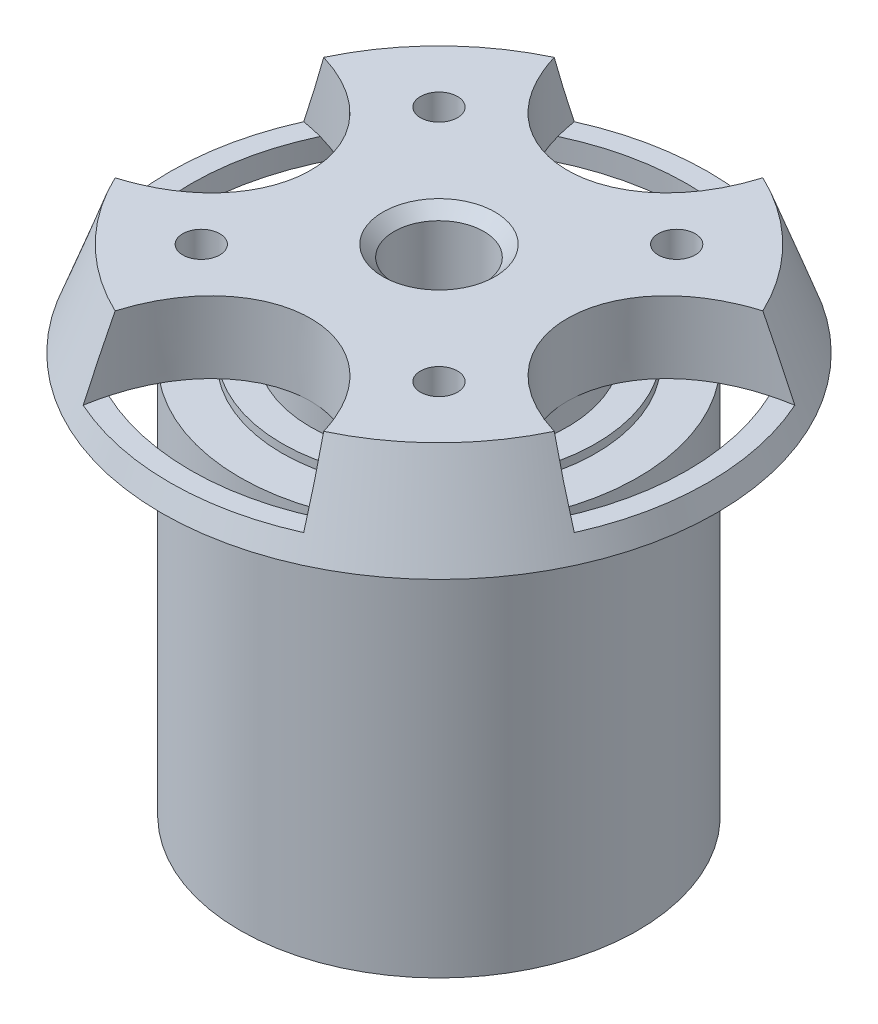
SolidWorks part; units mm, degrees
ref_plane "Front Plane" through (0, 0, 0) normal (0, 0, 1) x (1, 0, 0)
ref_plane "Top Plane" through (0, 0, 0) normal (0, 1, 0) x (1, 0, 0)
ref_plane "Right Plane" through (0, 0, 0) normal (1, 0, 0) x (0, 0, -1)
ref_axis "Axis1" through (0, 46.5537, 0) along (0, -1, 0)
sketch "Sketch2" plane through (0, 0, 0) normal (0, 0, 1) x (1, 0, 0)
  line L1 (0, 27.2574) -> (4, 27.2574)
  line L3 (4, 0) -> (21.6927, 0)
  line L4 (21.6927, 0) -> (24.75, -8.4)
  line L5 (24.75, -8.4) -> (14, -8.4)
  line L6 (14, -8.4) -> (14, -9.15)
  line L7 (14, -9.15) -> (17.75, -9.15)
  line L15 (17.75, -9.15) -> (17.75, -44.15)
  line L16 (17.75, -44.15) -> (4, -44.15)
  line L17 (4, -44.15) -> (4, 0)
  dimension "D3" = 0.75
  dimension "D5" = 4
  dimension "D7" = 8.4
  dimension "D9" = 27.2574
  dimension "D1" = 35
  dimension "D2" = 4
  dimension "D4" = 7
  dimension "D6" = 24.75
  dimension "D8" = 20
  dimension "D10" = 10
revolve "Revolve1" add sketch "Sketch2" angle 360 about axis through (0, 46.5537, 0) along (0, -1, 0)
hole_wizard "Tap Drill for M4x0.7 Tap1" positions "Sketch3" profile "Sketch4" hole size "M4x0.7" standard "ANSI Metric"
sketch "Sketch3" plane through (0, 0, 0) normal (0, 1, 0) x (1, 0, 0)
  line L1 (10.6066, 10.6066) -> (-10.6066, 10.6066)
  line L2 (10.6066, 10.6066) -> (10.6066, -10.6066)
  line L3 (10.6066, -10.6066) -> (-10.6066, -10.6066)
  line L4 (-10.6066, 10.6066) -> (-10.6066, -10.6066)
  line L5 (10.6066, 10.6066) -> (-10.6066, -10.6066) construction
  line L6 (10.6066, -10.6066) -> (-10.6066, 10.6066) construction
  point P0 (10.6066, -10.6066)
  point P2 (-10.6066, -10.6066)
  point P4 (-10.6066, 10.6066)
  point P6 (10.6066, 10.6066)
  point P62 (0, 0)
  dimension "D1" = 30
sketch "Sketch4" plane through (10.6066, 0, 10.6066) normal (1, 0, 0) x (0, 0, 1)
  line L0 (0, 0) -> (0, 8.9914)
  line L1 (0, 8.9914) -> (1.65, 8)
  line L2 (1.65, 8) -> (1.65, 0)
  line L5 (1.65, 0) -> (0, 0)
  line L10 (0, 8.9914) -> (-1.65, 8) construction
  line L11 (0, -6.35) -> (0, 107.95) construction
  dimension "Hole Dia." = 3.3
  dimension "Hole Depth" = 8
  dimension "Drill Angle" = 118
chamfer "Chamfer1" distance 1 angle 45 1 edges at (0, 0, 4)
sketch "Sketch5" plane through (0, -8.4, 0) normal (0, -1, 0) x (1, 0, 0)
  line L0 (0, 0) -> (0, 24.75) construction
  line L2 (9.95, 22.6619) -> (-9.95, 22.6619)
  circle A0 centre (0, 0) radius 24.75
  circle A1 centre (0, 0) radius 24.75 construction
  spline S0 degree 3 poles (9.95, 22.6619) (8.05, 7.7127) (-8.05, 7.7127) (-9.95, 22.6619) knots 0 0 0 0 1 1 1 1
  point P10 (0, 22.6619)
  point P15 (0, 11.45)
  dimension "D3" = 27
  dimension "D1" = 13.3
  dimension "D2" = 19.9
ref_plane "Plane1" through (0, -6.4, 0) normal (0, -1, 0) x (-1, 0, 0)
sketch "Sketch8" plane through (0, -6.4, 0) normal (0, -1, 0) x (-1, 0, 0)
  circle A0 centre (0, 0) radius 24.75 construction
  arc A1 (-9.95, -22.6619) -> (9.95, -22.6619) centre (0, 0) ccw
  spline S0 degree 3 poles (1837.9023, -763.0428) (-1985.2905, 239.0843) (1985.3043, 239.0809) (-1837.9407, -763.0529) knots -3.593761 -3.593761 -3.593761 -3.593761 4.593788 4.593788 4.593788 4.593788 only from (-9.95, -22.6619) to (9.95, -22.6619) construction
  spline S1 degree 3 poles (-9.95, -22.6619) (-8.05, -7.7127) (8.05, -7.7127) (9.95, -22.6619) knots 0 0 0 0 1 1 1 1
extrude "Cut-Extrude3" cut sketch "Sketch8" against normal through all
pattern_circular "CirPattern2" count 4 every 90 about axis through (0, 46.5537, 0) along (0, -1, 0) of "Cut-Extrude3"
sketch "Sketch9" plane through (0, -6.4, 0) normal (0, 1, 0) x (1, 0, 0)
  circle A0 centre (0, 0) radius 22.15
  circle A1 centre (0, 0) radius 11.45
  spline S0 degree 3 poles (-21.9137, 9.8411) (-7.9621, 7.5479) (-7.9621, -7.5479) (-21.9137, -9.8411) knots 0.01697 0.01697 0.01697 0.01697 0.98303 0.98303 0.98303 0.98303 construction
  dimension "D1" = 44.3
extrude "Cut-Extrude5" cut sketch "Sketch9" against normal blind 2
equation "\"WHEEL_SHAFT_LEN\"=27.2574"
equation "\"D9@Sketch2\"=\"WHEEL_SHAFT_LEN\""
equation "\"ENCODER_SHAFT_LEN\"=9.88617"
